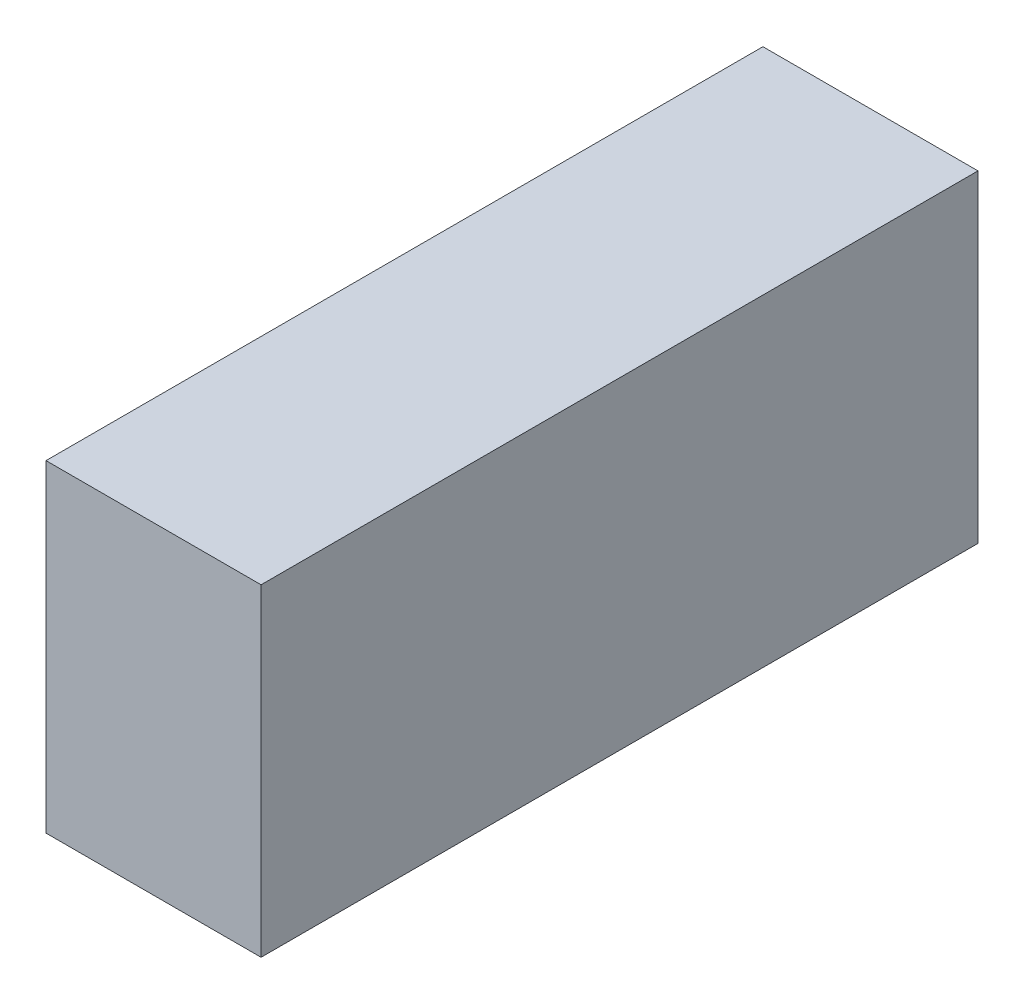
SolidWorks part; units mm, degrees
ref_plane "Plan de face" through (0, 0, 0) normal (0, 0, 1) x (1, 0, 0)
ref_plane "Plan de dessus" through (0, 0, 0) normal (0, 1, 0) x (1, 0, 0)
ref_plane "Plan de droite" through (0, 0, 0) normal (1, 0, 0) x (0, 0, -1)
sketch "Esquisse1" plane through (0, 0, 0) normal (0, 0, 1) x (1, 0, 0)
  line L1 (3.928, 90.5375) -> (63.928, 90.5375)
  line L2 (3.928, 90.5375) -> (3.928, 180.5375)
  line L3 (3.928, 180.5375) -> (63.928, 180.5375)
  line L4 (63.928, 90.5375) -> (63.928, 180.5375)
  dimension "D1" = 60
  dimension "D2" = 90
extrude "Boss.-Extru.1" add sketch "Esquisse1" along normal blind 200
sketch "Esquisse2" plane through (0, 0, 0) normal (0, 0, -1) x (-1, 0, 0)
  line L0 (-63.928, 105.5375) -> (-3.928, 105.5375) construction
  line L1 (-63.928, 90.5375) -> (-63.928, 180.5375) construction
  line L2 (-3.928, 180.5375) -> (-3.928, 90.5375) construction
  line L3 (-63.928, 165.5375) -> (-3.928, 165.5375) construction
  line L4 (-33.928, 90.5375) -> (-33.928, 105.5375) construction
  line L5 (-3.928, 90.5375) -> (-63.928, 90.5375) construction
  circle A0 centre (-57.928, 105.5375) radius 2.5
  circle A1 centre (-9.928, 105.5375) radius 2.5
  circle A2 centre (-9.928, 165.5375) radius 2.5
  circle A3 centre (-57.928, 165.5375) radius 2.5
  dimension "D2" = 5
  dimension "D1" = 15
  dimension "D3" = 60
  dimension "D4" = 48
extrude "Enlèv. mat.-Extru.1" cut sketch "Esquisse2" against normal blind 10
